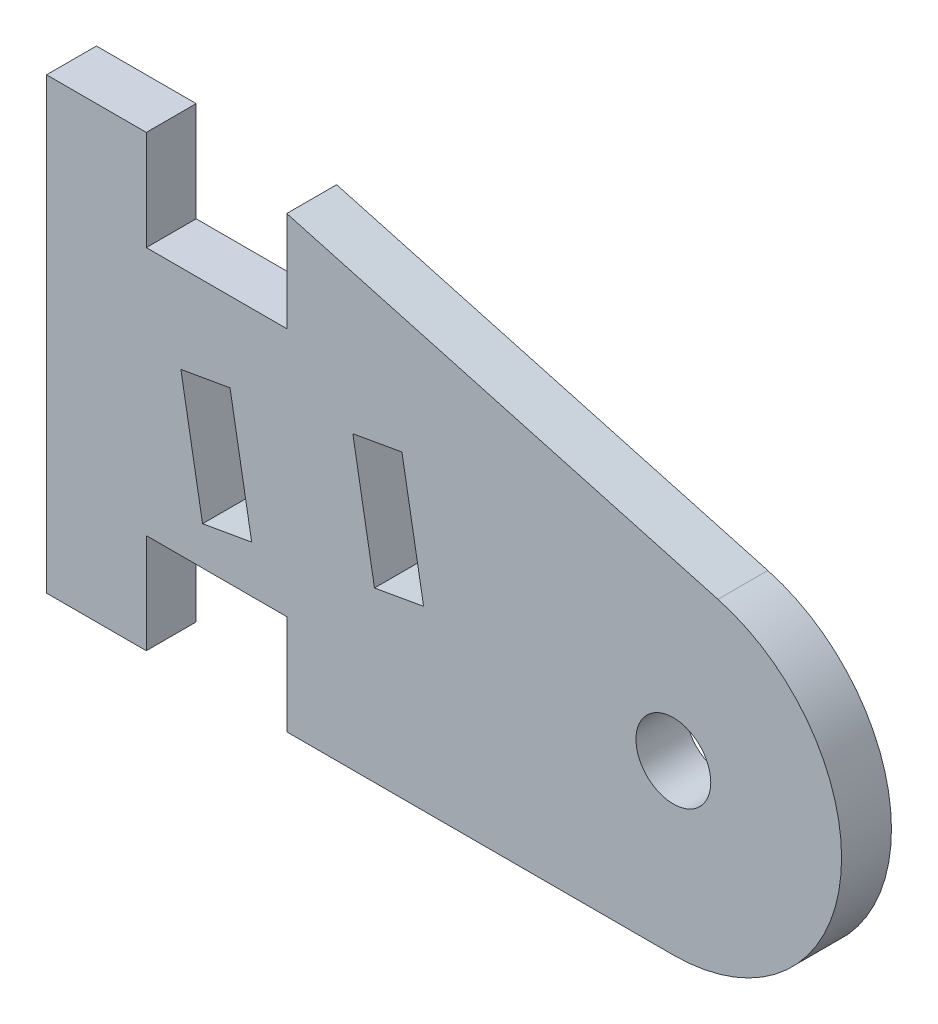
SolidWorks part; units mm, degrees
ref_plane "Front Plane" through (0, 0, 0) normal (0, 0, 1) x (1, 0, 0)
ref_plane "Top Plane" through (0, 0, 0) normal (0, 1, 0) x (1, 0, 0)
ref_plane "Right Plane" through (0, 0, 0) normal (1, 0, 0) x (0, 0, -1)
sketch "Sketch1" plane through (0, 0, 0) normal (0, 0, 1) x (1, 0, 0)
  line L0 (0, 0) -> (0, 18)
  line L1 (9.6315, -0.0004) -> (9.6315, 3.9996)
  line L2 (9.6315, 3.9996) -> (4, 3.9996)
  line L3 (9.6315, 18) -> (26.9204, 13.2486)
  line L4 (9.6315, 18) -> (9.6315, 14)
  line L5 (9.6315, 14) -> (4, 14)
  line L6 (0, 0) -> (4, 0)
  line L7 (4, 0) -> (4, 3.9996)
  line L9 (14.2505, 12.0256) -> (12.2808, 11.6783)
  line L10 (7.3568, 10.81) -> (8.225, 5.886)
  line L11 (7.3568, 10.81) -> (5.3872, 10.4627)
  line L12 (4, 18) -> (4, 14)
  line L13 (0, 18) -> (4, 18)
  line L14 (5.3872, 10.4627) -> (6.2554, 5.5387)
  line L15 (6.2554, 5.5387) -> (8.225, 5.886)
  line L16 (12.2808, 11.6783) -> (13.1491, 6.7542)
  line L17 (13.1491, 6.7542) -> (15.1187, 7.1015)
  line L18 (14.2505, 12.0256) -> (15.1187, 7.1015)
  line L20 (9.6315, -0.0004) -> (25.133, -0.0004)
  arc A1 (25.133, -0.0004) -> (26.9204, 13.2486) centre (25.133, 6.7447) ccw
  circle A5 centre (25.133, 6.7447) radius 1.5
  dimension "D16" = 6.745
  dimension "D15" = 3
  dimension "D2" = 18
  dimension "D3" = 5.6315
  dimension "D4" = 4
  dimension "D5" = 15.5015
  dimension "D6" = 4
  dimension "D7" = 4
  dimension "D8" = 3.9996
  dimension "D9" = 5
  dimension "D10" = 2
  dimension "D11" = 2
  dimension "D12" = 4
  dimension "D13" = 5
  dimension "D14" = 5
extrude "Boss-Extrude1" add sketch "Sketch1" along normal blind 2
